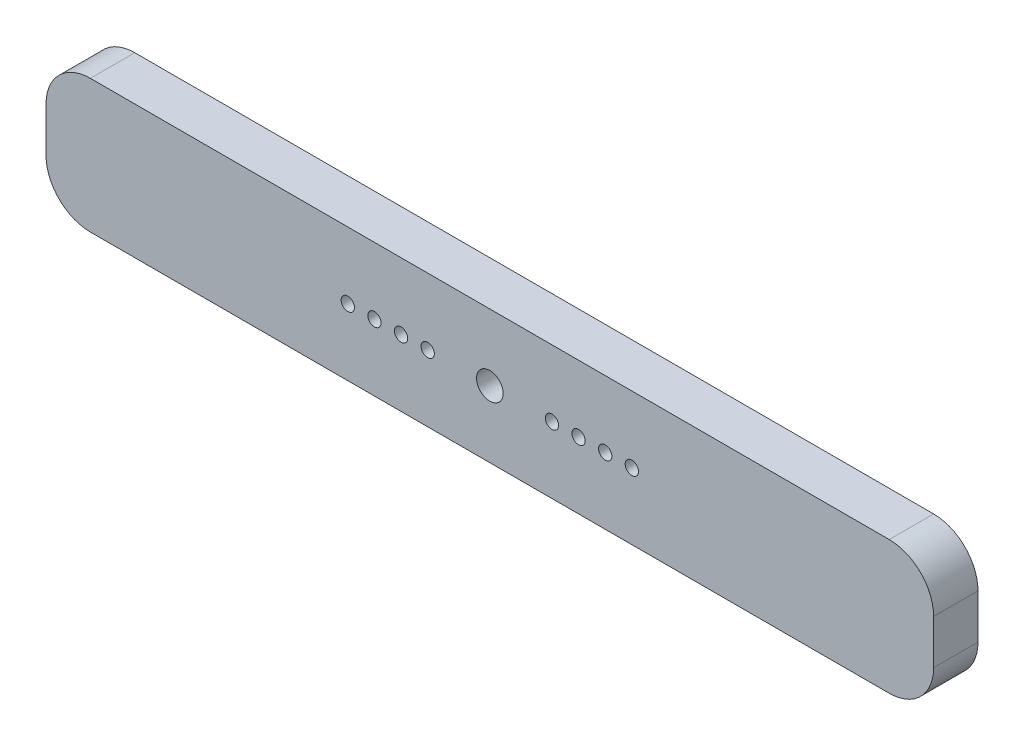
SolidWorks part; units mm, degrees
ref_plane "Front Plane" through (0, 0, 0) normal (0, 0, 1) x (1, 0, 0)
ref_plane "Top Plane" through (0, 0, 0) normal (0, 1, 0) x (1, 0, 0)
ref_plane "Right Plane" through (0, 0, 0) normal (1, 0, 0) x (0, 0, -1)
sketch "Sketch2" plane through (0, 0, 0) normal (0, 0, 1) x (1, 0, 0)
  line L1 (-133.1313, 10) -> (16.8687, 10)
  line L2 (-133.1313, 10) -> (-133.1313, -5)
  line L3 (-133.1313, -5) -> (16.8687, -5)
  line L4 (16.8687, 10) -> (16.8687, -5)
  dimension "D1" = 15
  dimension "D2" = 10
  dimension "D3" = 150
extrude "Boss-Extrude1" add sketch "Sketch2" along normal blind 5
fillet "Fillet2" radius 5 4 edges at (-133.1313, 10, 2.5) (-133.1313, -5, 2.5) (16.8687, -5, 2.5) (16.8687, 10, 2.5)
sketch "Sketch6" plane through (0, 0, 0) normal (0, 0, 1) x (1, 0, 0)
  line L1 (11.8687, 10) -> (-128.1313, 10) construction
  line L2 (11.8687, 10) -> (-128.1313, 10) construction
  line L3 (-58.1313, 10) -> (-58.1313, -5) construction
  line L4 (-128.1313, -5) -> (11.8687, -5) construction
  line L5 (16.8687, 0) -> (16.8687, 5) construction
  circle A0 centre (-58.1313, 2.5) radius 1.5
  circle A1 centre (-51.1313, 2.5) radius 0.75
  circle A2 centre (-48.1313, 2.5) radius 0.75
  circle A3 centre (-45.1313, 2.5) radius 0.75
  circle A5 centre (-65.1313, 2.5) radius 0.75
  circle A6 centre (-68.1313, 2.5) radius 0.75
  circle A7 centre (-71.1313, 2.5) radius 0.75
  circle A9 centre (-74.1313, 2.5) radius 0.75
  circle A11 centre (-42.1313, 2.5) radius 0.75
  dimension "D1" = 1.5
  dimension "D2" = 1.5
  dimension "D3" = 1.5
  dimension "D4" = 1.5
  dimension "D5" = 7
  dimension "D6" = 3
  dimension "D7" = 3
  dimension "D8" = 7.5
  dimension "D9" = 7.5
  dimension "D10" = 7.5
  dimension "D11" = 7.5
  dimension "D12" = 3
  dimension "D13" = 75
extrude "Cut-Extrude4" cut sketch "Sketch6" along normal through all
sketch "Sketch7" plane through (0, 0, 0) normal (0, 0, 1) x (1, 0, 0)
  line L0 (-128.1313, -5) -> (11.8687, -5) construction
  line L1 (-133.1313, 10) -> (-108.1313, 10)
  line L2 (-133.1313, 10) -> (-133.1313, -5)
  line L3 (-133.1313, -5) -> (-108.1313, -5)
  line L4 (-108.1313, 10) -> (-108.1313, -5)
  line L5 (11.8687, 10) -> (-128.1313, 10) construction
  line L6 (-8.1313, 10) -> (22.2334, 10)
  line L7 (-8.1313, 10) -> (-8.1313, -5)
  line L8 (-8.1313, -5) -> (22.2334, -5)
  line L9 (22.2334, 10) -> (22.2334, -5)
  point P12 (-58.1313, 2.5)
  dimension "D1" = 100
  dimension "D2" = 50
extrude "Cut-Extrude6" cut sketch "Sketch7" along normal blind 45
fillet "Fillet3" radius 5 4 edges at (-8.1313, 10, 2.5) (-8.1313, -5, 2.5) (-108.1313, -5, 2.5) (-108.1313, 10, 2.5)
